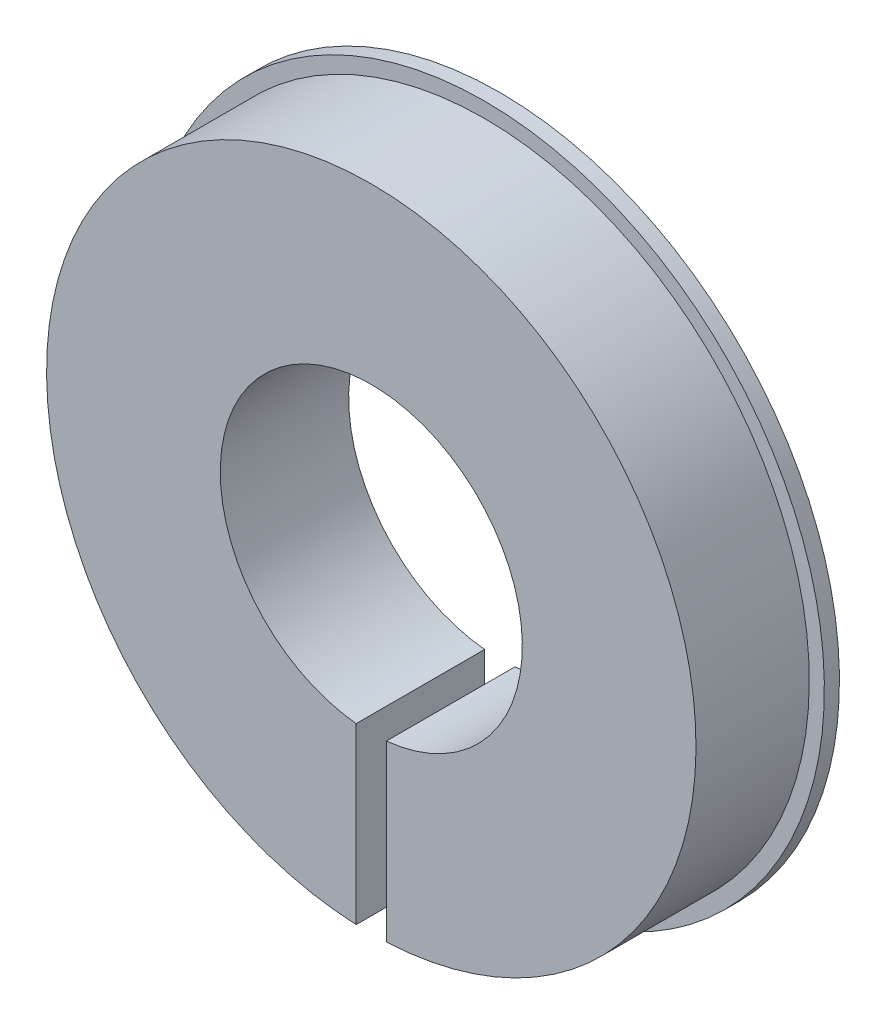
SolidWorks part; units mm, degrees
ref_plane "Płaszczyzna przednia" through (0, 0, 0) normal (0, 0, 1) x (1, 0, 0)
ref_plane "Płaszczyzna górna" through (0, 0, 0) normal (0, 1, 0) x (1, 0, 0)
ref_plane "Płaszczyzna prawa" through (0, 0, 0) normal (1, 0, 0) x (0, 0, -1)
sketch "Szkic2" plane through (0, 0, 0) normal (0, 0, 1) x (1, 0, 0)
  circle A0 centre (0, 0) radius 22.5
extrude "Dodanie-wyciągnięcie1" add sketch "Szkic2" along normal blind 1
sketch "Szkic3" plane through (0, 0, 1) normal (0, 0, 1) x (1, 0, 0)
  circle A0 centre (0, 0) radius 21.5
extrude "Dodanie-wyciągnięcie2" add sketch "Szkic3" along normal blind 7.5
sketch "Szkic4" plane through (0, 0, 8.5) normal (0, 0, 1) x (1, 0, 0)
  line L0 (0, 0) -> (0, -23.6586) construction
  line L1 (-1, -9.9499) -> (-1, -23.6586)
  line L2 (1, -9.9499) -> (1, -23.6586)
  line L3 (-1, 0) -> (-1, -23.6586) construction
  line L4 (1, 0) -> (1, -23.6586) construction
  line L5 (-1, -23.6586) -> (1, -23.6586)
  arc A0 (1, -9.9499) -> (-1, -9.9499) centre (0, 0) ccw
  dimension "D1" = 1
  dimension "D2" = 1
extrude "Wytnij-wyciągnięcie1" cut sketch "Szkic4" against normal blind 10
